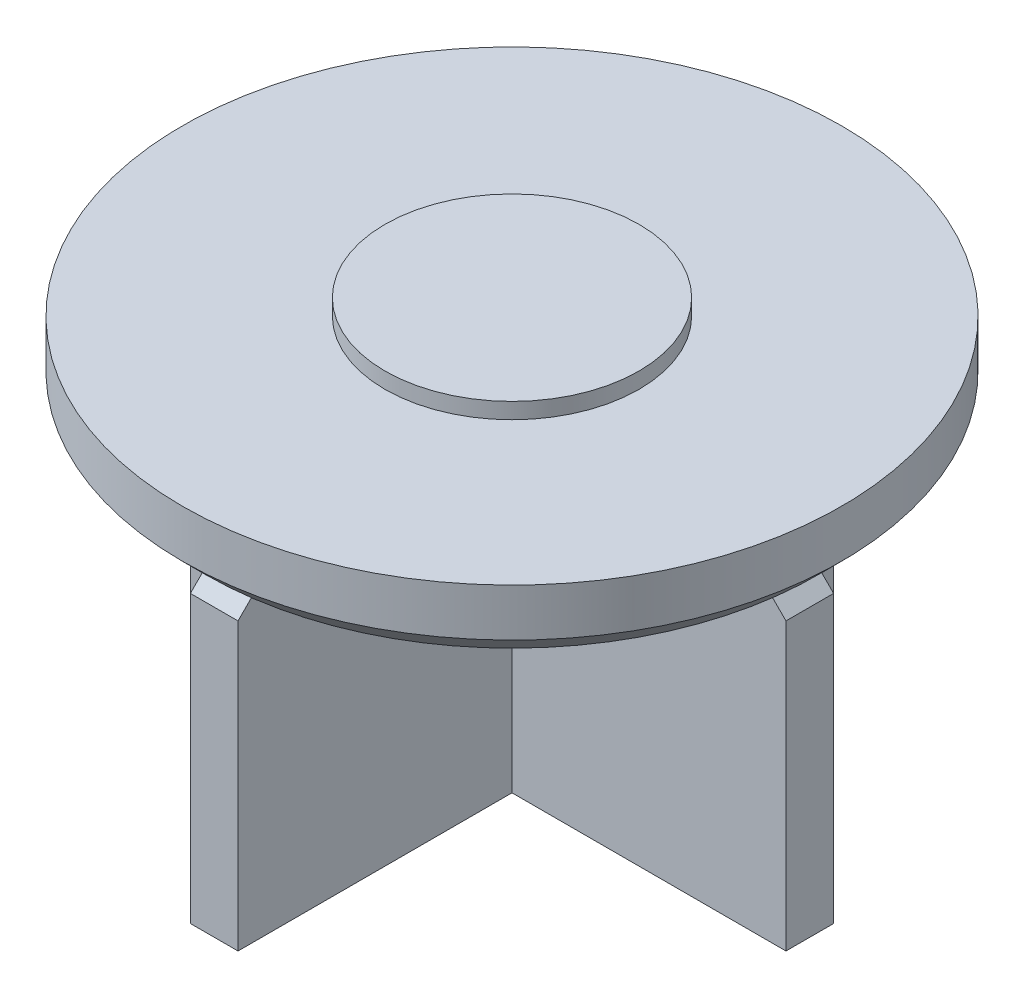
SolidWorks part; units mm, degrees
ref_plane "Front Plane" through (0, 0, 0) normal (0, 0, 1) x (1, 0, 0)
ref_plane "Top Plane" through (0, 0, 0) normal (0, 1, 0) x (1, 0, 0)
ref_plane "Right Plane" through (0, 0, 0) normal (1, 0, 0) x (0, 0, -1)
sketch "Sketch1" plane through (0, 0, 0) normal (0, 1, 0) x (1, 0, 0)
  line L0 (3, 3) -> (37.5, 3)
  line L1 (-37.5, 3) -> (-3, 3)
  line L2 (-37.5, 3) -> (-37.5, -3)
  line L3 (-37.5, -3) -> (-3, -3)
  line L4 (37.5, 3) -> (37.5, -3)
  line L5 (-37.5, 3) -> (37.5, -3) construction
  line L6 (-37.5, -3) -> (37.5, 3) construction
  line L7 (-3, 37.5) -> (3, 37.5)
  line L8 (-3, 37.5) -> (-3, 3)
  line L9 (-3, -37.5) -> (3, -37.5)
  line L10 (3, 37.5) -> (3, 3)
  line L11 (-3, 37.5) -> (3, -37.5) construction
  line L12 (-3, -37.5) -> (3, 37.5) construction
  line L13 (4.836, 0) -> (0, 0) construction
  line L14 (3, -3) -> (3, -37.5)
  line L15 (3, -3) -> (37.5, -3)
  line L16 (-3, -3) -> (-3, -37.5)
  line L17 (0, 0) -> (0, 6.6848) construction
  point P0 (0, 0)
  point P6 (0, 0)
  dimension "D1" = 75
  dimension "D2" = 75
  dimension "D3" = 6
  dimension "D4" = 6
extrude "Boss-Extrude1" add sketch "Sketch1" along normal blind 40
chamfer "Chamfer1" distance 4 angle 45 4 edges at (-37.5, 40, 0) (0, 40, -37.5) (37.5, 40, 0) (0, 40, 37.5)
sketch "Sketch3" plane through (0, 40, 0) normal (0, 1, 0) x (1, 0, 0)
  circle A0 centre (0, 0) radius 41.5
  dimension "D1" = 83
extrude "Boss-Extrude2" add sketch "Sketch3" along normal blind 9
sketch "Sketch4" plane through (0, 49, 0) normal (0, 1, 0) x (1, 0, 0)
  circle A0 centre (0, 0) radius 16
  dimension "D1" = 32
extrude "Boss-Extrude3" add sketch "Sketch4" along normal blind 2
chamfer "Chamfer2" distance 3 angle 45 1 edges at (0, 40, 41.5)
